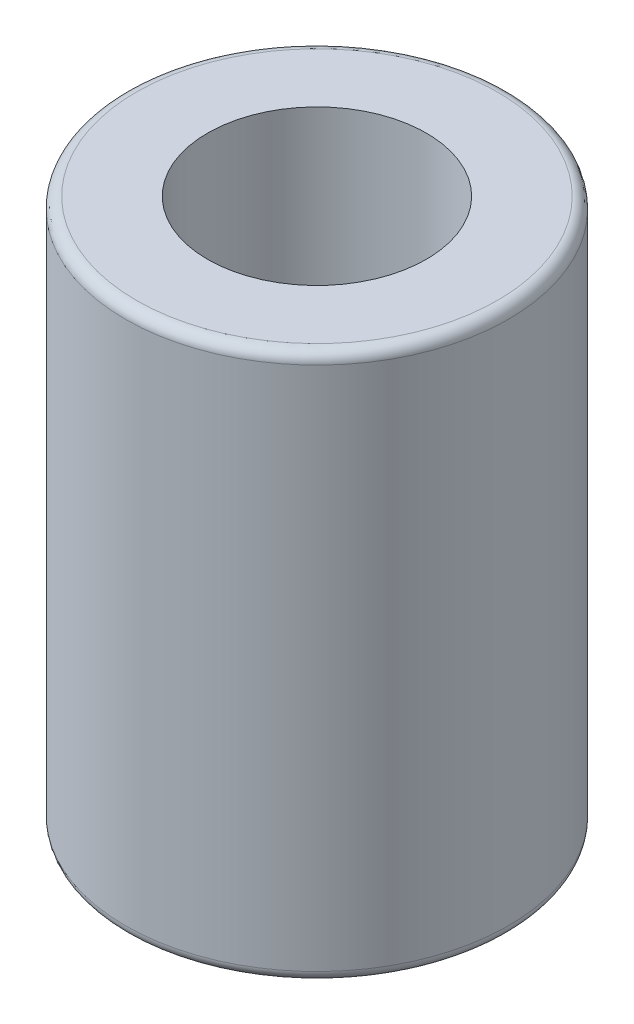
SolidWorks part; units mm, degrees
material "6063-O，挤压棒材(SS)"
ref_plane "前视基准面" through (0, 0, 0) normal (0, 0, 1) x (1, 0, 0)
ref_plane "上视基准面" through (0, 0, 0) normal (0, 1, 0) x (1, 0, 0)
ref_plane "右视基准面" through (0, 0, 0) normal (1, 0, 0) x (0, 0, -1)
sketch "草图1" plane through (0, 0, 0) normal (0, 1, 0) x (1, 0, 0)
  circle A0 centre (0, 0) radius 3.5
  circle A1 centre (0, 0) radius 2
  dimension "D1" = 7
  dimension "D2" = 4
extrude "凸台-拉伸1" add sketch "草图1" along normal mid plane 10
fillet "圆角1" radius 0.2 2 edges at (0, -5, 3.5) (0, 5, 3.5)
other "冻结***"
